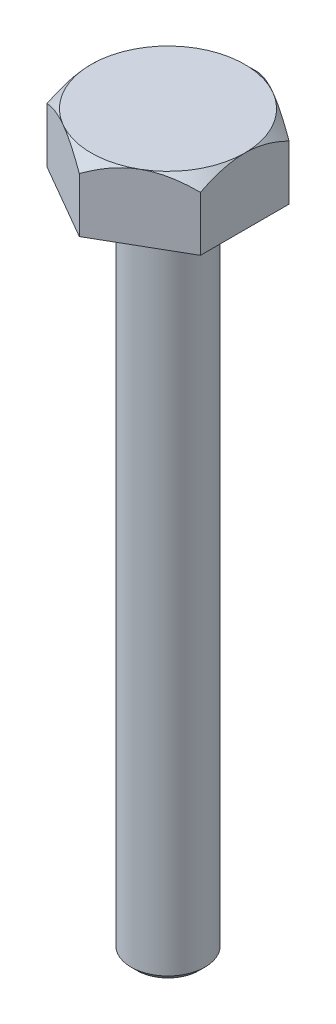
SolidWorks part; units mm, degrees
ref_plane "Front Plane" through (0, 0, 0) normal (0, 0, 1) x (1, 0, 0)
ref_plane "Top Plane" through (0, 0, 0) normal (0, 1, 0) x (1, 0, 0)
ref_plane "Right Plane" through (0, 0, 0) normal (1, 0, 0) x (0, 0, -1)
sketch "Sketch5" plane through (0, 0, 0) normal (0, 1, 0) x (1, 0, 0)
  line L1 (13.208, -7.6256) -> (13.208, 7.6256)
  line L2 (13.208, 7.6256) -> (0, 15.2513)
  line L3 (0, 15.2513) -> (-13.208, 7.6256)
  line L4 (-13.208, 7.6256) -> (-13.208, -7.6256)
  line L5 (-13.208, -7.6256) -> (0, -15.2513)
  line L6 (0, -15.2513) -> (13.208, -7.6256)
  circle A0 centre (0, 0) radius 13.208 construction
  dimension "D1" = 26.416
extrude "Boss-Extrude2" add sketch "Sketch5" along normal blind 11.43
sketch "Sketch7" plane through (0, 11.43, 0) normal (0, 1, 0) x (1, 0, 0)
  line L0 (13.208, 7.6256) -> (0, 15.2513) construction
  circle A0 centre (0, 0) radius 13.208
ref_plane "Plane1" through (0, 0, -15.2513) normal (-0.866, 0, -0.5) x (-0.5, 0, 0.866)
extrude "Cut-Extrude1" cut sketch "Sketch7" against normal blind 11.43 draft 45 flip side to cut
sketch "Sketch9" plane through (0, 0, 0) normal (0, -1, 0) x (-1, 0, 0)
  circle A0 centre (0, 0) radius 6.35
  dimension "D1" = 12.7
extrude "Boss-Extrude6" add sketch "Sketch9" along normal blind 114.3
cosmetic thread "Cosmetic Thread1" parameters "D1"=63.5, "D2"=11.1887
chamfer "Chamfer3" distance 1.016 angle 45 1 edges at (0, -114.3, -6.35)
